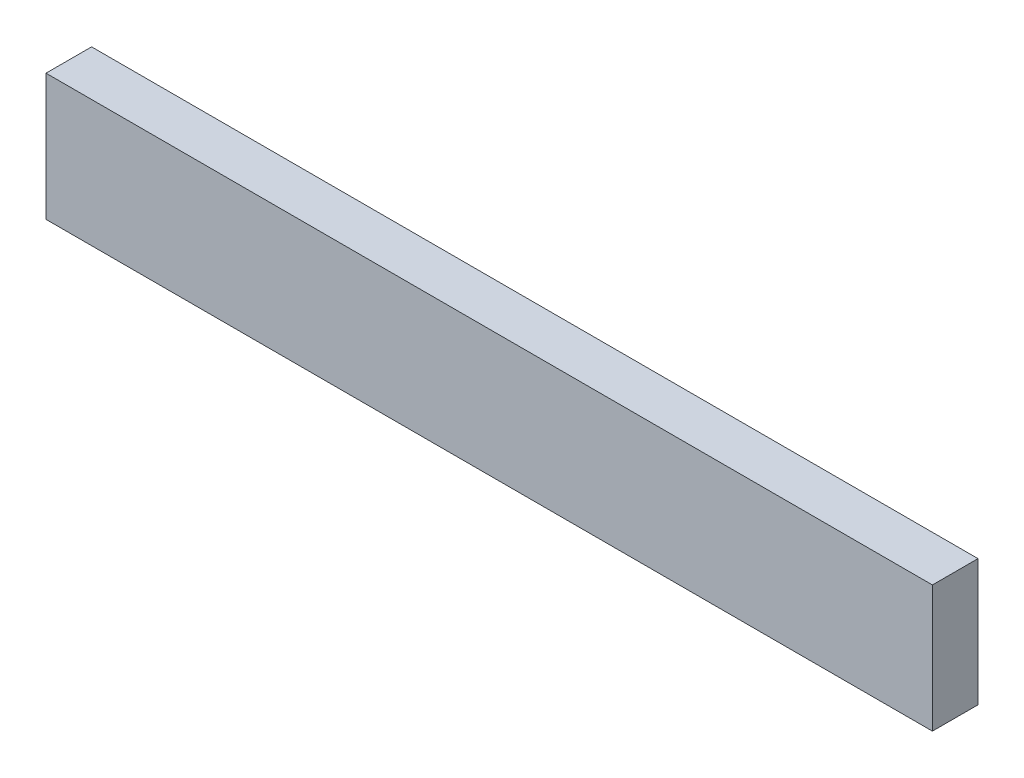
SolidWorks part; units mm, degrees
ref_plane "Front Plane" through (0, 0, 0) normal (0, 0, 1) x (1, 0, 0)
ref_plane "Top Plane" through (0, 0, 0) normal (0, 1, 0) x (1, 0, 0)
ref_plane "Right Plane" through (0, 0, 0) normal (1, 0, 0) x (0, 0, -1)
sketch "Sketch1" plane through (0, 0, 0) normal (0, 0, 1) x (1, 0, 0)
  line L1 (0, 0) -> (350, 0)
  line L2 (0, 0) -> (0, 50)
  line L3 (0, 50) -> (350, 50)
  line L4 (350, 0) -> (350, 50)
  dimension "D1" = 50
  dimension "D2" = 350
extrude "Boss-Extrude1" add sketch "Sketch1" along normal blind 18
